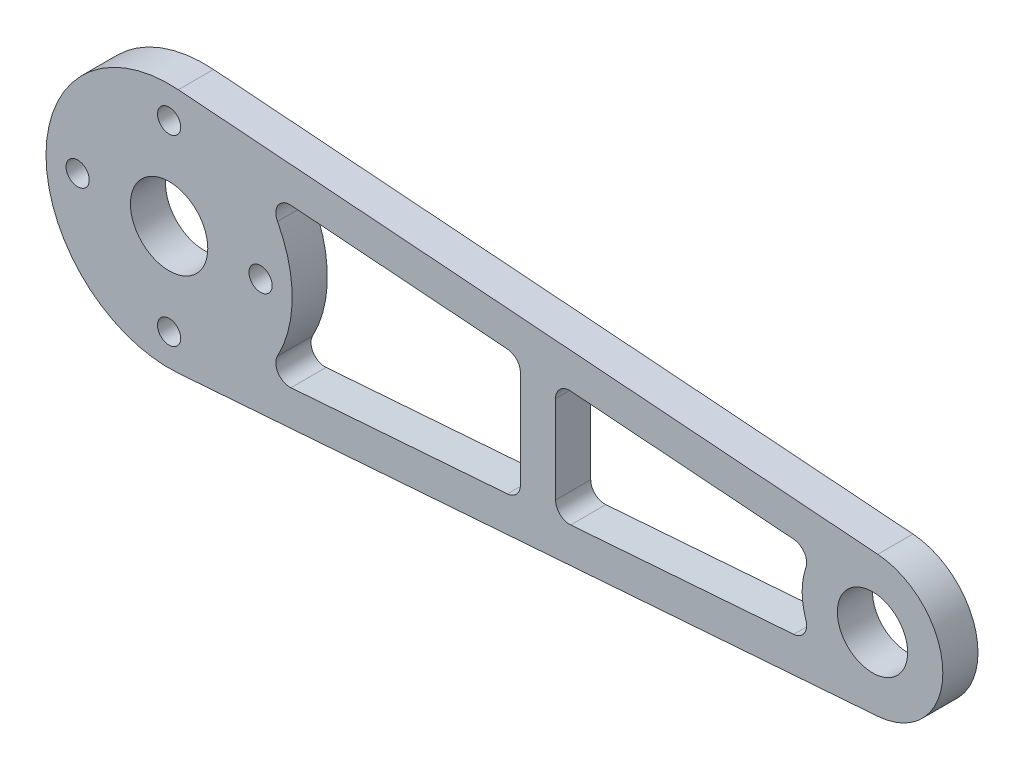
SolidWorks part; units mm, degrees
ref_plane "Front" through (0, 0, 0) normal (0, 0, 1) x (1, 0, 0)
ref_plane "Top" through (0, 0, 0) normal (0, 1, 0) x (1, 0, 0)
ref_plane "Right" through (0, 0, 0) normal (1, 0, 0) x (0, 0, -1)
sketch "草图2" plane through (0, 0, 0) normal (0, 0, 1) x (1, 0, 0)
  line L0 (1.3125, 17.4507) -> (100.75, 9.9718)
  line L1 (1.3125, -17.4507) -> (100.75, -9.9718)
  line L2 (17.3229, -11.2324) -> (48.0948, -8.918)
  line L3 (17.3229, 11.2324) -> (48.0948, 8.918)
  line L4 (57.0948, 8.2411) -> (88.7888, 5.8573)
  line L5 (54.9448, 6.2467) -> (54.9448, -6.2467)
  line L6 (49.9448, 6.9236) -> (49.9448, -6.9236)
  line L7 (57.0948, -8.2411) -> (88.7888, -5.8573)
  arc A0 (1.3125, 17.4507) -> (1.3125, -17.4507) centre (0, 0) ccw
  arc A1 (90.5323, 3.2191) -> (90.5323, -3.2191) centre (100, 0) ccw
  circle A2 centre (0, 0) radius 5.5
  circle A3 centre (100, 0) radius 5
  circle A4 centre (0, 13) radius 1.65
  circle A5 centre (13, 0) radius 1.65
  circle A6 centre (0, -13) radius 1.65
  circle A7 centre (-13, 0) radius 1.65
  arc A8 (15.4116, -8.2906) -> (15.4116, 8.2906) centre (0, 0) ccw
  arc A9 (100.75, -9.9718) -> (100.75, 9.9718) centre (100, 0) ccw
  arc A10 (90.5323, -3.2191) -> (88.7888, -5.8573) centre (88.6388, -3.863) cw
  arc A11 (90.5323, 3.2191) -> (88.7888, 5.8573) centre (88.6388, 3.863) ccw
  arc A12 (54.9448, 6.2467) -> (57.0948, 8.2411) centre (56.9448, 6.2467) cw
  arc A13 (57.0948, -8.2411) -> (54.9448, -6.2467) centre (56.9448, -6.2467) cw
  arc A14 (49.9448, -6.9236) -> (48.0948, -8.918) centre (47.9448, -6.9236) cw
  arc A15 (48.0948, 8.918) -> (49.9448, 6.9236) centre (47.9448, 6.9236) cw
  arc A16 (15.4116, -8.2906) -> (17.3229, -11.2324) centre (17.1729, -9.2381) ccw
  arc A17 (15.4116, 8.2906) -> (17.3229, 11.2324) centre (17.1729, 9.2381) cw
  point P22 (0, 0)
  point P32 (54.9448, 8.4028)
  point P35 (54.9448, -8.4028)
  point P42 (13.1505, -11.5462)
  dimension "D1" = 35
  dimension "D2" = 20
  dimension "D4" = 11
  dimension "D5" = 10
  dimension "D6" = 3.3
  dimension "D11" = 2
  dimension "D3" = 100
  dimension "D7" = 13
  dimension "D9" = 5
  dimension "D10" = 5
  dimension "D8" = 4
extrude "凸台-拉伸1" add sketch "草图2" along normal blind 5
